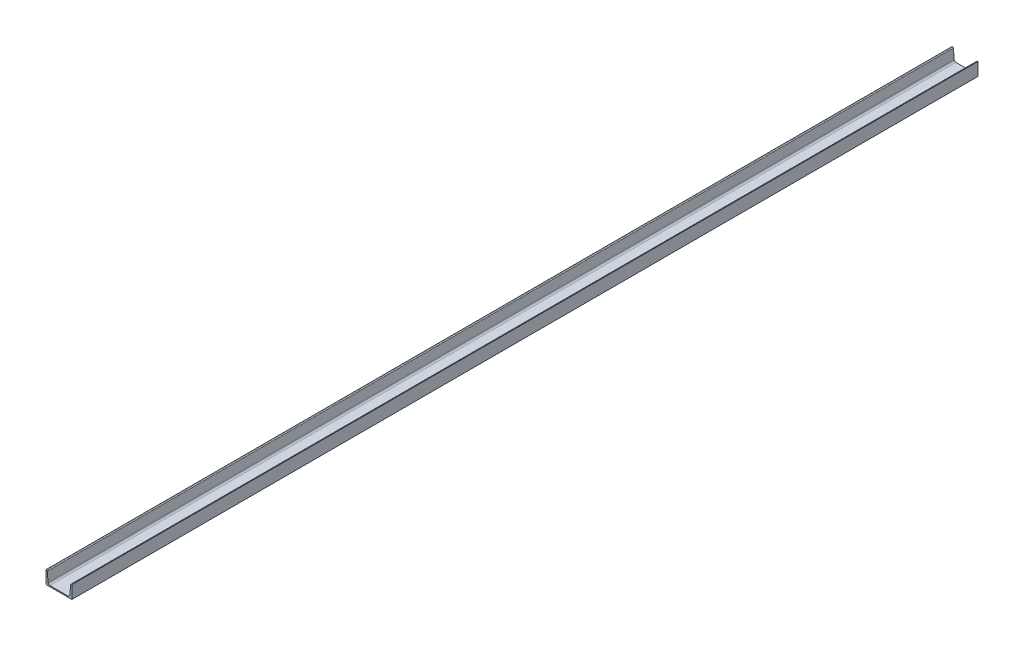
SolidWorks part; units mm, degrees
ref_plane "Front Plane" through (0, 0, 0) normal (0, 0, 1) x (1, 0, 0)
ref_plane "Top Plane" through (0, 0, 0) normal (0, 1, 0) x (1, 0, 0)
ref_plane "Right Plane" through (0, 0, 0) normal (1, 0, 0) x (0, 0, -1)
sketch "Sketch1" plane through (0, 0, 0) normal (1, 0, 0) x (0, 0, -1)
  line L0 (-2625, 0) -> (2625, 0)
  dimension "D1" = 5250
ref_plane "Plane1" through (0, 0, 2625) normal (0, 0, -1) x (0, 1, 0)
other "Channel C 150 X 75 X 6.5(1)"
ref_plane "Plane2" through (0, 0, 2625) normal (0, 0, -1) x (0, 1, 0)
sketch "Sketch11" plane through (0, 0, 2625) normal (0, 0, -1) x (0, 1, 0)
  line L0 (75, 150) -> (0, 150)
  line L1 (75, 0) -> (0, 0)
  line L2 (0, 150) -> (0, 0)
  line L5 (0, 10) -> (40.75, 10) construction
  line L6 (75, 150) -> (75, 147.5781)
  line L7 (75, 0) -> (75, 2.4219)
  line L8 (6.5, 75) -> (0, 75) construction
  line L12 (6.5, 127.8402) -> (6.5, 22.1598)
  line L17 (15.6284, 137.8021) -> (70.4358, 142.5972)
  line L18 (15.6284, 12.1979) -> (70.4358, 7.4028)
  arc A0 (70.4358, 142.5972) -> (75, 147.5781) centre (70, 147.5781) ccw
  arc A1 (70.4358, 7.4028) -> (75, 2.4219) centre (70, 2.4219) cw
  arc A9 (6.5, 22.1598) -> (15.6284, 12.1979) centre (16.5, 22.1598) ccw
  arc A10 (6.5, 127.8402) -> (15.6284, 137.8021) centre (16.5, 127.8402) cw
  point P10 (37.5, 150)
  point P11 (37.5, 0)
  point P14 (0, 0)
  dimension "D4" = 34.25
  dimension "RI" = 10
  dimension "D2" = 5
  dimension "RA" = 5
  dimension "Depth" = 150
  dimension "BF" = 75
  dimension "TW" = 6.5
  dimension "TF" = 10
